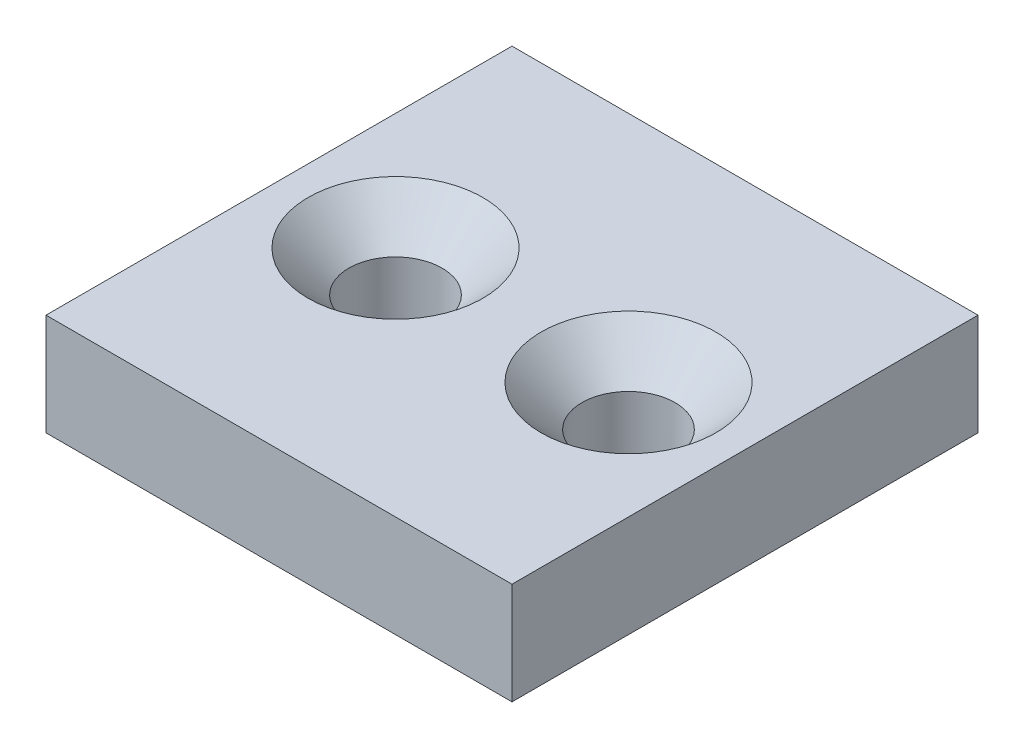
SolidWorks part; units mm, degrees
ref_plane "Front Plane" through (0, 0, 0) normal (0, 0, 1) x (1, 0, 0)
ref_plane "Top Plane" through (0, 0, 0) normal (0, 1, 0) x (1, 0, 0)
ref_plane "Right Plane" through (0, 0, 0) normal (1, 0, 0) x (0, 0, -1)
sketch "Sketch1" plane through (0, 0, 0) normal (0, 1, 0) x (1, 0, 0)
  line L1 (-16, -16) -> (16, -16)
  line L2 (-16, -16) -> (-16, 16)
  line L3 (-16, 16) -> (16, 16)
  line L4 (16, -16) -> (16, 16)
  line L5 (-16, -16) -> (16, 16) construction
  line L6 (-16, 16) -> (16, -16) construction
  point P0 (0, 0)
  dimension "D1" = 32
extrude "Boss-Extrude1" add sketch "Sketch1" along normal blind 7
hole_wizard "CSK for M6 Flat Head Machine Screw1" positions "Sketch2" profile "Sketch4" countersink size "M6" standard "ANSI Metric" end condition up to next
sketch "Sketch2" plane through (0, 7, 0) normal (0, 1, 0) x (1, 0, 0)
  line L0 (-16, 16) -> (-16, -16) construction
  point P0 (8, 0)
  point P2 (-8, 0)
  point P4 (0, 0)
  point P10 (-1.5477, -7.4641)
  point P13 (0, 0)
  dimension "D1" = 16
  dimension "D2" = 8
sketch "Sketch4" plane through (8, 7, 0) normal (1, 0, 0) x (0, 0, 1)
  line L0 (0, 0) -> (0, 7)
  line L1 (0, 7) -> (3.2, 7)
  line L2 (3.2, 7) -> (3.2, 2.8)
  line L3 (3.2, 2.8) -> (6, 0)
  line L5 (6, 0) -> (0, 0)
  line L6 (-3.2, 2.8) -> (-6, 0) construction
  line L11 (0, -6.35) -> (0, 107.95) construction
  dimension "Thru Hole Dia." = 6.4
  dimension "Thru Hole Depth" = 7
  dimension "Near C'Sink Dia." = 12
  dimension "Near C'Sink Angle" = 90
